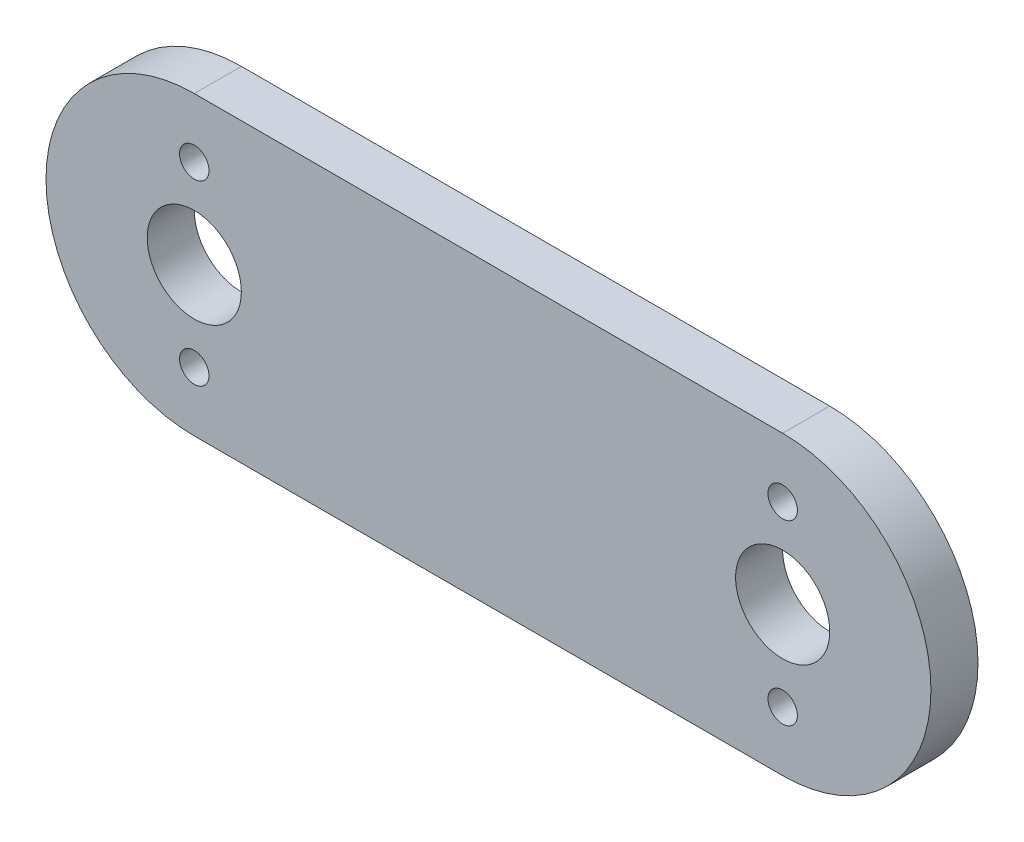
SolidWorks part; units mm, degrees
material "PLA"
ref_plane "Front Plane" through (0, 0, 0) normal (0, 0, 1) x (1, 0, 0)
ref_plane "Top Plane" through (0, 0, 0) normal (0, 1, 0) x (1, 0, 0)
ref_plane "Right Plane" through (0, 0, 0) normal (1, 0, 0) x (0, 0, -1)
sketch "Sketch1" plane through (0, 0, 0) normal (0, 0, 1) x (1, 0, 0)
  line L0 (0, 12.6) -> (50, 12.6)
  line L1 (0, -12.6) -> (50, -12.6)
  circle A0 centre (0, 0) radius 4
  arc A1 (0, 12.6) -> (0, -12.6) centre (0, 0) ccw
  circle A2 centre (50, 0) radius 4
  arc A3 (50, 12.6) -> (50, -12.6) centre (50, 0) cw
  circle A4 centre (0, 7.55) radius 1.25
  circle A5 centre (0, -7.55) radius 1.25
  circle A6 centre (50, 7.55) radius 1.25
  circle A7 centre (50, -7.55) radius 1.25
  dimension "D2" = 8
  dimension "D3" = 8
  dimension "D4" = 12.6
  dimension "D6" = 2.5
  dimension "D7" = 2.5
  dimension "D8" = 2.5
  dimension "D9" = 2.5
  dimension "D1" = 25.2
  dimension "D5" = 50
  dimension "D10" = 7.55
  dimension "D11" = 7.55
  dimension "D12" = 7.55
  dimension "D13" = 7.55
extrude "Boss-Extrude1" add sketch "Sketch1" along normal blind 4
